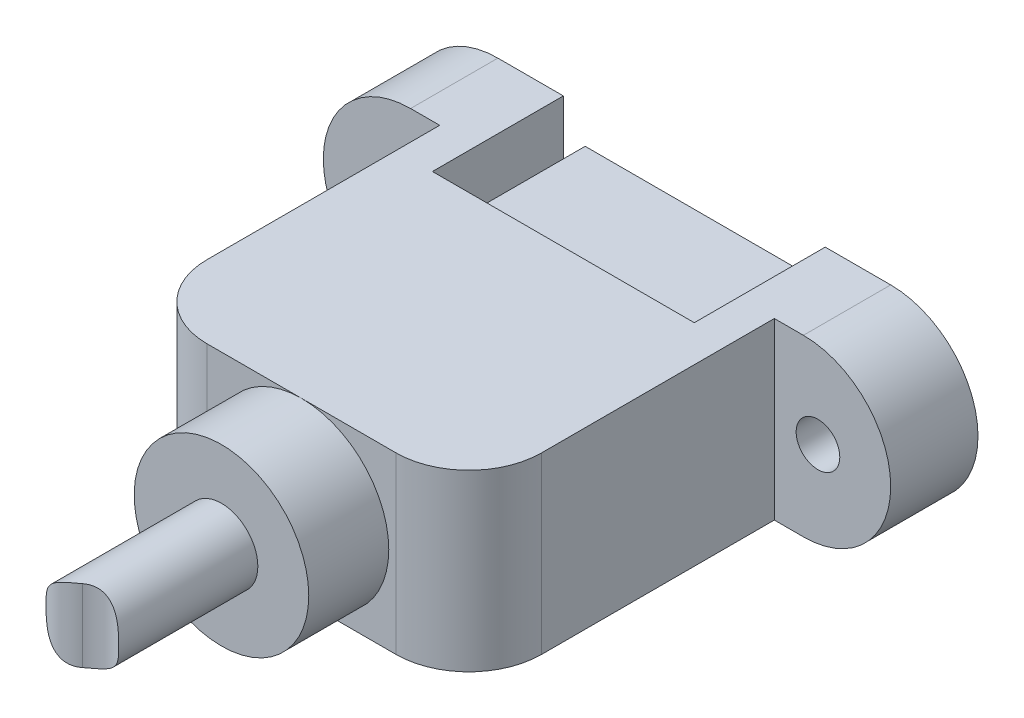
SolidWorks part; units mm, degrees
material "ABS"
ref_plane "Přední rovina" through (0, 0, 0) normal (0, 0, 1) x (1, 0, 0)
ref_plane "Horní rovina" through (0, 0, 0) normal (0, 1, 0) x (1, 0, 0)
ref_plane "Pravá rovina" through (0, 0, 0) normal (1, 0, 0) x (0, 0, -1)
sketch "Skica1" plane through (0, 0, 0) normal (0, 1, 0) x (1, 0, 0)
  line L0 (-11.5, 0) -> (11.5, 0)
  line L1 (-6.5, -18) -> (6.5, -18)
  line L2 (11.5, 0) -> (11.5, -13)
  line L3 (0, 0) -> (0, -18) construction
  line L4 (-11.5, 0) -> (-11.5, -13)
  arc A0 (6.5, -18) -> (11.5, -13) centre (6.5, -13) ccw
  arc A1 (-6.5, -18) -> (-11.5, -13) centre (-6.5, -13) cw
  dimension "D3" = 5
  dimension "D1" = 18
  dimension "D2" = 23
extrude "Přidat vysunutím1" add sketch "Skica1" along normal mid plane 12
sketch "Skica2" plane through (0, 0, 0) normal (0, 0, -1) x (-1, 0, 0)
  line L0 (-11.5, -6) -> (11.5, -6) construction
  line L1 (11.5, 6) -> (9, 6)
  line L2 (11.5, 6) -> (11.5, -6)
  line L3 (11.5, -6) -> (9, -6)
  line L4 (9, 6) -> (9, -6)
  line L5 (0, 0) -> (0, 8.0226) construction
  line L6 (-9, 6) -> (-9, -6)
  line L7 (-11.5, -6) -> (-9, -6)
  line L8 (-11.5, 6) -> (-11.5, -6)
  line L9 (-11.5, 6) -> (-9, 6)
  dimension "D1" = 2.5
extrude "Přidat vysunutím2" add sketch "Skica2" along normal blind 9
sketch "Skica3" plane through (0, 0, -9) normal (0, 0, -1) x (-1, 0, 0)
  line L0 (11.5, 6) -> (13.5, 6)
  line L1 (9, 6) -> (9, -6) construction
  line L2 (13.5, -6) -> (11.5, -6)
  line L3 (9, -6) -> (11.5, -6) construction
  line L4 (11.5, 6) -> (11.5, -6)
  line L5 (0, 0) -> (0, 11.1178) construction
  line L6 (-11.5, 6) -> (-11.5, -6)
  line L7 (-13.5, -6) -> (-11.5, -6)
  line L8 (-11.5, 6) -> (-13.5, 6)
  arc A0 (13.5, 6) -> (13.5, -6) centre (13.5, 0) cw
  arc A1 (-13.5, 6) -> (-13.5, -6) centre (-13.5, 0) ccw
  circle A2 centre (-14.5, 0) radius 1.5
  circle A3 centre (14.5, 0) radius 1.5
  dimension "D2" = 3
  dimension "D3" = 29
  dimension "D1" = 10.5
extrude "Přidat vysunutím3" add sketch "Skica3" against normal blind 6
sketch "Skica5" plane through (0, 0, 18) normal (0, 0, 1) x (1, 0, 0)
  line L0 (-6.5, 6) -> (6.5, 6) construction
  circle A0 centre (0, 0) radius 6
extrude "Přidat vysunutím4" add sketch "Skica5" along normal blind 5.5
sketch "Skica6" plane through (0, 0, 0) normal (0, 0, -1) x (-1, 0, 0)
  line L0 (0, 0) -> (0, 9.5804) construction
  line L1 (0, 0) -> (-8.2507, 0) construction
  line L2 (6.5, 2.75) -> (6.5, -2.75)
  line L3 (-6.5, -2.75) -> (6.5, -2.75)
  line L4 (-6.5, 2.75) -> (-6.5, -2.75)
  line L5 (-7.5, 3.75) -> (7.5, 3.75)
  line L6 (-7.5, 3.75) -> (-7.5, -3.75)
  line L7 (-7.5, -3.75) -> (7.5, -3.75)
  line L8 (7.5, 3.75) -> (7.5, -3.75)
  line L9 (-6.5, 2.75) -> (6.5, 2.75)
  dimension "D1" = 15
  dimension "D2" = 7.5
  dimension "D3" = 1
extrude "Přidat vysunutím5" add sketch "Skica6" along normal up to surface (9 mm away) separate body up to face at (12.75, 0, -9)
sketch "Skica7" plane through (0, 0, 0) normal (0, 0, -1) x (-1, 0, 0)
  line L0 (6.5, -2.75) -> (-6.5, -2.75) construction
  line L1 (-5.5, 0.25) -> (5.5, 0.25)
  line L2 (-5.5, 0.25) -> (-5.5, -1.75)
  line L3 (-5.5, -1.75) -> (5.5, -1.75)
  line L4 (5.5, 0.25) -> (5.5, -1.75)
  line L5 (-6.5, -2.75) -> (-6.5, 2.75) construction
  line L6 (6.5, 2.75) -> (6.5, -2.75) construction
  dimension "D1" = 2
  dimension "D2" = 1
  dimension "D3" = 1
  dimension "D4" = 1
extrude "Přidat vysunutím7" add sketch "Skica7" along normal up to surface (9 mm away) separate body up to face at (12.75, 0, -9)
sketch "Skica8" plane through (0, 0, 23.5) normal (0, 0, 1) x (1, 0, 0)
  circle A0 centre (0, 0) radius 2.5
  dimension "D1" = 5
extrude "Přidat vysunutím8" add sketch "Skica8" along normal blind 10
sketch "Skica9" plane through (0, 0, 0) normal (0, 1, 0) x (1, 0, 0)
  line L0 (-2.5, -23.5) -> (-2.5, -33.5) construction
  line L2 (2.5, -33.5) -> (2.5, -23.5) construction
  line L3 (0, -33.0612) -> (0, -30.1817) construction
  line L4 (-2.5, -33.5) -> (2.5, -33.5) construction
  arc A0 (-2.5, -33.0612) -> (0, -33.0612) centre (-1.25, -31.5) ccw
  arc A1 (0, -33.0612) -> (2.5, -33.0612) centre (1.25, -34.6225) cw
  dimension "D1" = 2
extrude "Odebrat vysunutím2" cut sketch "Skica9" against normal through all and the other way through all flip side to cut
